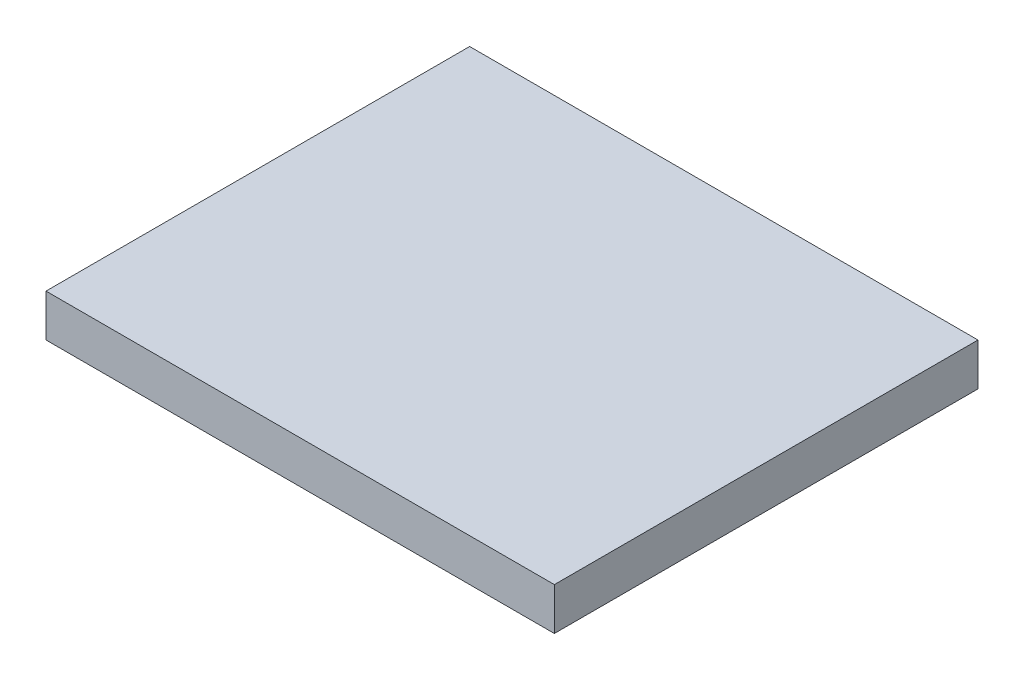
SolidWorks part; units mm, degrees
ref_plane "Front Plane" through (0, 0, 0) normal (0, 0, 1) x (1, 0, 0)
ref_plane "Top Plane" through (0, 0, 0) normal (0, 1, 0) x (1, 0, 0)
ref_plane "Right Plane" through (0, 0, 0) normal (1, 0, 0) x (0, 0, -1)
sketch "Sketch1" plane through (0, 0, 0) normal (0, 1, 0) x (1, 0, 0)
  line L1 (-60, 50) -> (60, 50)
  line L2 (-60, 50) -> (-60, -50)
  line L3 (-60, -50) -> (60, -50)
  line L4 (60, 50) -> (60, -50)
  line L5 (-60, 50) -> (60, -50) construction
  line L6 (-60, -50) -> (60, 50) construction
  point P0 (0, 0)
  dimension "D1" = 120
  dimension "D2" = 100
extrude "Boss-Extrude1" add sketch "Sketch1" along normal blind 10
